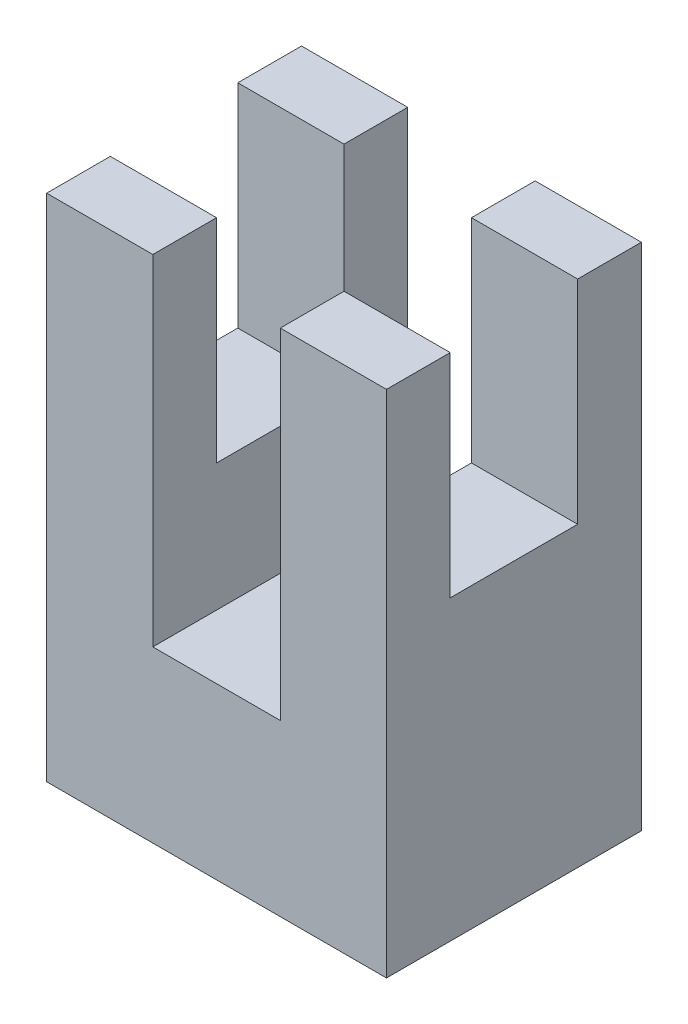
SolidWorks part; units mm, degrees
ref_plane "Alzado" through (0, 0, 0) normal (0, 0, 1) x (1, 0, 0)
ref_plane "Planta" through (0, 0, 0) normal (0, 1, 0) x (1, 0, 0)
ref_plane "Vista lateral" through (0, 0, 0) normal (1, 0, 0) x (0, 0, -1)
sketch "Croquis1" plane through (0, 0, 0) normal (0, 0, 1) x (1, 0, 0)
  line L0 (-20, 0) -> (20, 0)
  line L1 (20, 0) -> (20, 60)
  line L2 (20, 60) -> (7.5, 60)
  line L3 (7.5, 60) -> (7.5, 20)
  line L4 (7.5, 20) -> (-7.5, 20)
  line L5 (-7.5, 20) -> (-7.5, 60)
  line L6 (-7.5, 60) -> (-20, 60)
  line L7 (-20, 60) -> (-20, 0)
  point P4 (0, 0)
  point P10 (0, 0)
  point P11 (0, 0)
  dimension "D1" = 15
  dimension "D2" = 40
  dimension "D3" = 60
  dimension "D4" = 40
extrude "Saliente-Extruir1" add sketch "Croquis1" along normal mid plane 30
sketch "Croquis2" plane through (20, 0, 0) normal (1, 0, 0) x (0, 0, -1)
  line L0 (-7.5, 60) -> (-7.5, 35)
  line L1 (-15, 60) -> (15, 60) construction
  line L2 (-7.5, 35) -> (7.5, 35)
  line L3 (7.5, 35) -> (7.5, 60)
  line L4 (7.5, 60) -> (-7.5, 60)
  point P6 (0, 35)
  dimension "D1" = 15
  dimension "D2" = 25
extrude "Cortar-Extruir1" cut sketch "Croquis2" against normal up to next
mirror "Simetría1" about plane through (0, 0, 0) normal (1, 0, 0) of "Cortar-Extruir1"
